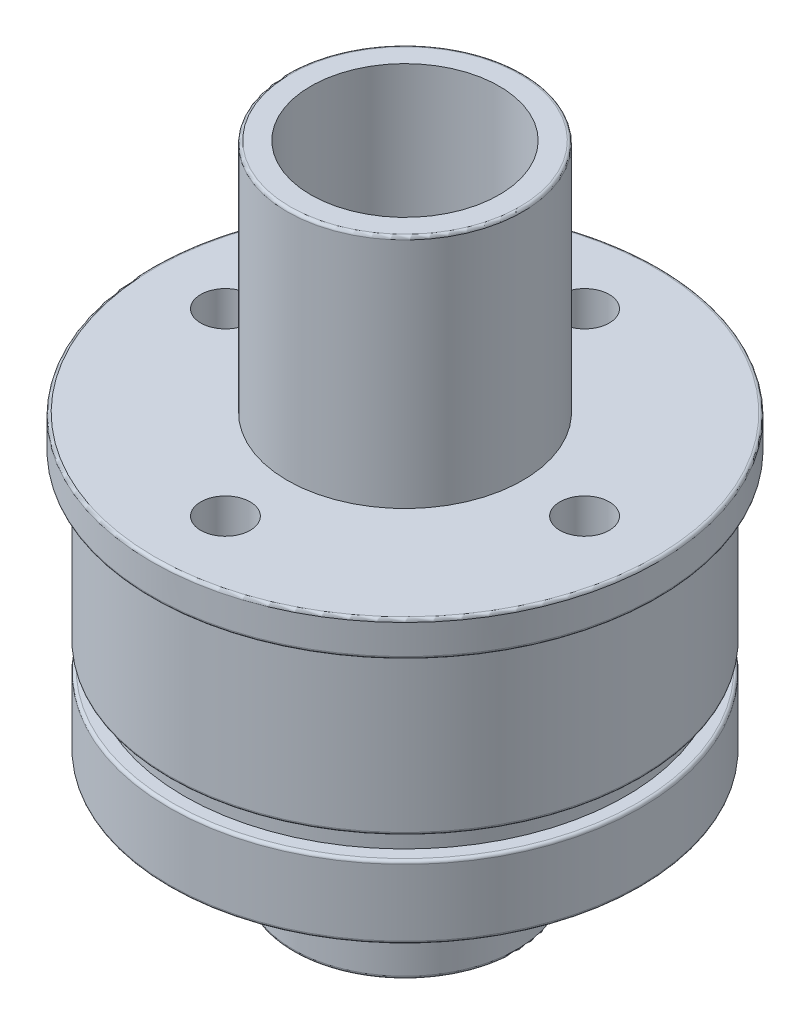
SolidWorks part; units mm, degrees
material "1.0037 (S235JR)"
ref_plane "Front Plane" through (0, 0, 0) normal (0, 0, 1) x (1, 0, 0)
ref_plane "Top Plane" through (0, 0, 0) normal (0, 1, 0) x (1, 0, 0)
ref_plane "Right Plane" through (0, 0, 0) normal (1, 0, 0) x (0, 0, -1)
sketch "Sketch1" plane through (0, 0, 0) normal (0, 0, 1) x (1, 0, 0)
  line L0 (21.5, 49) -> (0, 49)
  line L1 (0, 49) -> (0, 46)
  line L2 (0, 46) -> (21.5, 46)
  line L3 (21.5, 46) -> (21.5, 49)
  line L4 (0, 49) -> (0, 46) construction
revolve "Revolve1" add sketch "Sketch1" angle 360 about L4
sketch "Sketch2" plane through (0, 46, 0) normal (0, -1, 0) x (1, 0, 0)
  circle A0 centre (0, 0) radius 20
extrude "Boss-Extrude1" add sketch "Sketch2" along normal blind 17
sketch "Sketch3" plane through (0, 29, 0) normal (0, -1, 0) x (1, 0, 0)
  circle A0 centre (0, 0) radius 9.5
  dimension "D1" = 19
extrude "Boss-Extrude2" add sketch "Sketch3" along normal blind 15
sketch "Sketch4" plane through (0, 49, 0) normal (0, 1, 0) x (-1, 0, 0)
  circle A0 centre (0, 0) radius 10
  dimension "D1" = 20
extrude "Boss-Extrude3" add sketch "Sketch4" along normal blind 20
sketch "Sketch8" plane through (0, 29, 0) normal (0, -1, 0) x (1, 0, 0)
  circle A2 centre (0, 0) radius 20 construction
  circle A3 centre (0, 0) radius 20
  circle A4 centre (0, 0) radius 9.5
extrude "Boss-Extrude4" add sketch "Sketch8" along normal blind 5
sketch "Sketch10" plane through (0, 24, 0) normal (0, -1, 0) x (1, 0, 0)
  line L0 (0, 0) -> (-18.1364, 18.1364) construction
  circle A0 centre (0, 0) radius 15
  dimension "D1" = 30
fillet "Fillet1" radius 0.25 4 edges at (0, 24, -20) (0, 46, -21.5) (0, 49, -21.5) (0, 69, 10)
ref_plane "Plane1" through (0, 32, 0) normal (0, -1, 0) x (-1, 0, 0)
sketch "Sketch17" plane through (0, 32, 0) normal (0, -1, 0) x (-1, 0, 0)
  circle A0 centre (0, 0) radius 18.75
  circle A1 centre (0, 0) radius 29.1215
  dimension "D1" = 37.5
extrude "Cut-Extrude4" cut sketch "Sketch17" along normal blind 1.85
fillet "Fillet6" radius 0.25 3 edges at (0, 14, -9.5) (0, 30.15, -20) (0, 32, -20)
hole_wizard "M5 Gewindebohrung2" positions "Skizze1" profile "Skizze2" tap size "M5" standard "DIN"
sketch "Skizze1" plane through (0, 24, 0) normal (0, -1, 0) x (-1, 0, 0)
  line L1 (10.5, 10.5) -> (-10.5, 10.5) construction
  line L2 (10.5, 10.5) -> (10.5, -10.5) construction
  line L3 (10.5, -10.5) -> (-10.5, -10.5) construction
  line L4 (-10.5, 10.5) -> (-10.5, -10.5) construction
  line L5 (10.5, 10.5) -> (-10.5, -10.5) construction
  line L6 (10.5, -10.5) -> (-10.5, 10.5) construction
  point P1 (0, 0)
  point P2 (-10.5, -10.5)
  point P97 (10.5, 10.5)
  point P98 (10.5, -10.5)
  point P99 (-10.5, 10.5)
  dimension "D1" = 21
  dimension "D2" = 21
sketch "Skizze2" plane through (0, 24, 0) normal (1, 0, 0) x (0, 0, -1)
  line L0 (0, 0) -> (0, 13.6618)
  line L1 (0, 13.6618) -> (2.1, 12.4)
  line L2 (2.1, 12.4) -> (2.1, 0.425)
  line L3 (2.1, 0.425) -> (2.525, 0)
  line L5 (2.525, 0) -> (0, 0)
  line L6 (-2.1, 0.425) -> (-2.525, 0) construction
  line L10 (0, 13.6618) -> (-2.1, 12.4) construction
  line L11 (0, -6.35) -> (0, 107.95) construction
  dimension "Bohrerdurchmesser" = 4.2
  dimension "Bohrungstiefe" = 12.4
  dimension "Senkdurchmesser (Oben)" = 5.05
  dimension "Senkwinkel (Oben)" = 90
  dimension "Spitzenwinkel" = 118
cosmetic thread "Bohrungsgewinde10" parameters "D1"=10, "D2"=5
cosmetic thread "Bohrungsgewinde11" parameters "D1"=10, "D2"=5
cosmetic thread "Bohrungsgewinde12" parameters "D1"=10, "D2"=5
cosmetic thread "Bohrungsgewinde13" parameters "D1"=10, "D2"=5
hole_wizard "M5 Gewindebohrung1" positions "Skizze3" profile "Skizze4" tap size "M5" standard "DIN"
sketch "Skizze3" plane through (0, 49, 0) normal (0, 1, 0) x (1, 0, 0)
  line L0 (0, 22.3397) -> (0, -23.8425) construction
  line L2 (-25.0274, 0) -> (35.0268, 0) construction
  circle A0 centre (0, 0) radius 15.25 construction
  point P12 (29.0734, 17.0799)
  point P14 (0, 15.25)
  point P16 (15.25, 0)
  point P18 (0, -15.25)
  point P20 (-15.25, 0)
  dimension "D1" = 30.5
sketch "Skizze4" plane through (-15.25, 49, 0) normal (1, 0, 0) x (0, 0, 1)
  line L0 (0, 0) -> (0, 21.2618)
  line L1 (0, 21.2618) -> (2.1, 20)
  line L2 (2.1, 20) -> (2.1, 0)
  line L5 (2.1, 0) -> (0, 0)
  line L10 (0, 21.2618) -> (-2.1, 20) construction
  line L11 (0, -6.35) -> (0, 107.95) construction
  dimension "Bohrerdurchmesser" = 4.2
  dimension "Bohrungstiefe" = 20
  dimension "Spitzenwinkel" = 118
cosmetic thread "Bohrungsgewinde14" parameters "D1"=18, "D2"=5
cosmetic thread "Bohrungsgewinde15" parameters "D1"=18, "D2"=5
cosmetic thread "Bohrungsgewinde16" parameters "D1"=18, "D2"=5
cosmetic thread "Bohrungsgewinde17" parameters "D1"=18, "D2"=5
sketch "Skizze5" plane through (0, 0, 0) normal (0, 0, 1) x (1, 0, 0)
  line L0 (8, 69) -> (8, 39)
  line L3 (9.75, 69) -> (-9.75, 69) construction
  line L4 (8, 39) -> (7, 39)
  line L5 (7, 39) -> (7, 14)
  line L6 (-9.5, 14) -> (9.5, 14) construction
  line L8 (0, -23.65) -> (0, 23.65) construction
  line L13 (8, 69) -> (0, 69)
  line L14 (0, 69) -> (0, 14)
  line L15 (0, 14) -> (7, 14)
  line L16 (0, 62.7654) -> (0, -49937.2346) construction
  point P13 (0, 74)
  point P14 (0, 14)
  dimension "D1" = 8
  dimension "D2" = 7
  dimension "D3" = 30
revolve "Schnitt-Rotation1" cut sketch "Skizze5" angle 360 about L16
sketch "Skizze6" plane through (0, 69, 0) normal (0, 1, 0) x (1, 0, 0)
  circle A0 centre (0, 0) radius 8
extrude "Schnitt-Linear austragen1" cut sketch "Skizze6" against normal through all both and the other way through all
